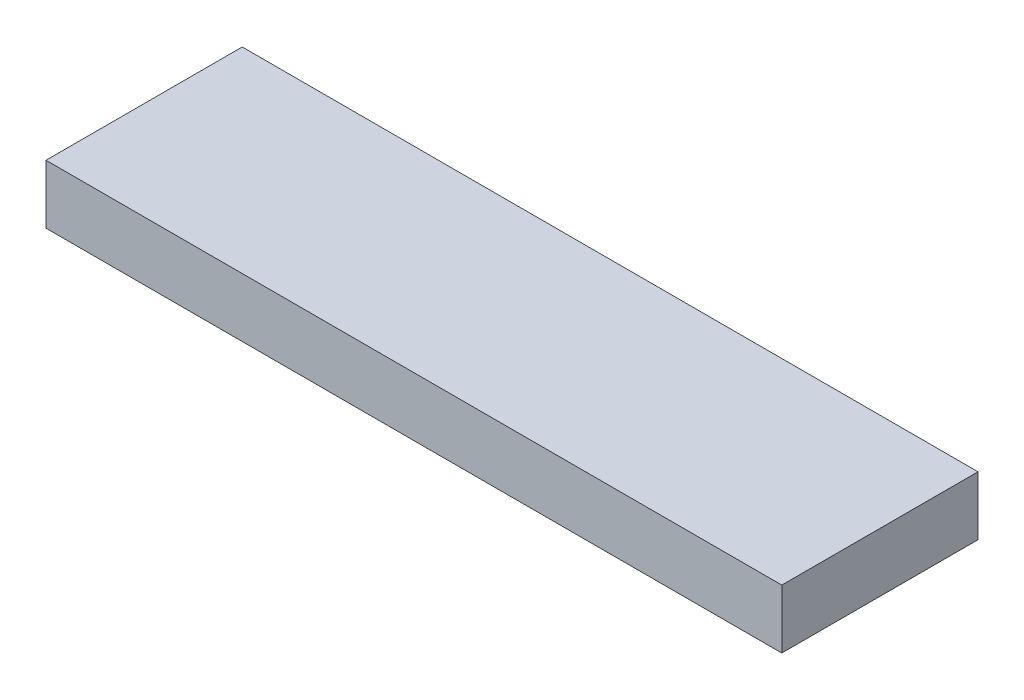
SolidWorks part; units mm, degrees
material "Acrílico (médio-alto impacto)"
ref_plane "Plano frontal" through (0, 0, 0) normal (0, 0, 1) x (1, 0, 0)
ref_plane "Plano superior" through (0, 0, 0) normal (0, 1, 0) x (1, 0, 0)
ref_plane "Plano direito" through (0, 0, 0) normal (1, 0, 0) x (0, 0, -1)
sketch "Esboço1" plane through (0, 0, 0) normal (0, 1, 0) x (1, 0, 0)
  line L1 (-75, -20) -> (75, -20)
  line L2 (-75, -20) -> (-75, 20)
  line L3 (-75, 20) -> (75, 20)
  line L4 (75, -20) -> (75, 20)
  line L5 (-75, -20) -> (75, 20) construction
  line L6 (-75, 20) -> (75, -20) construction
  point P0 (0, 0)
  dimension "D1" = 150
  dimension "D2" = 40
extrude "Ressalto-extrusão1" add sketch "Esboço1" along normal blind 12
